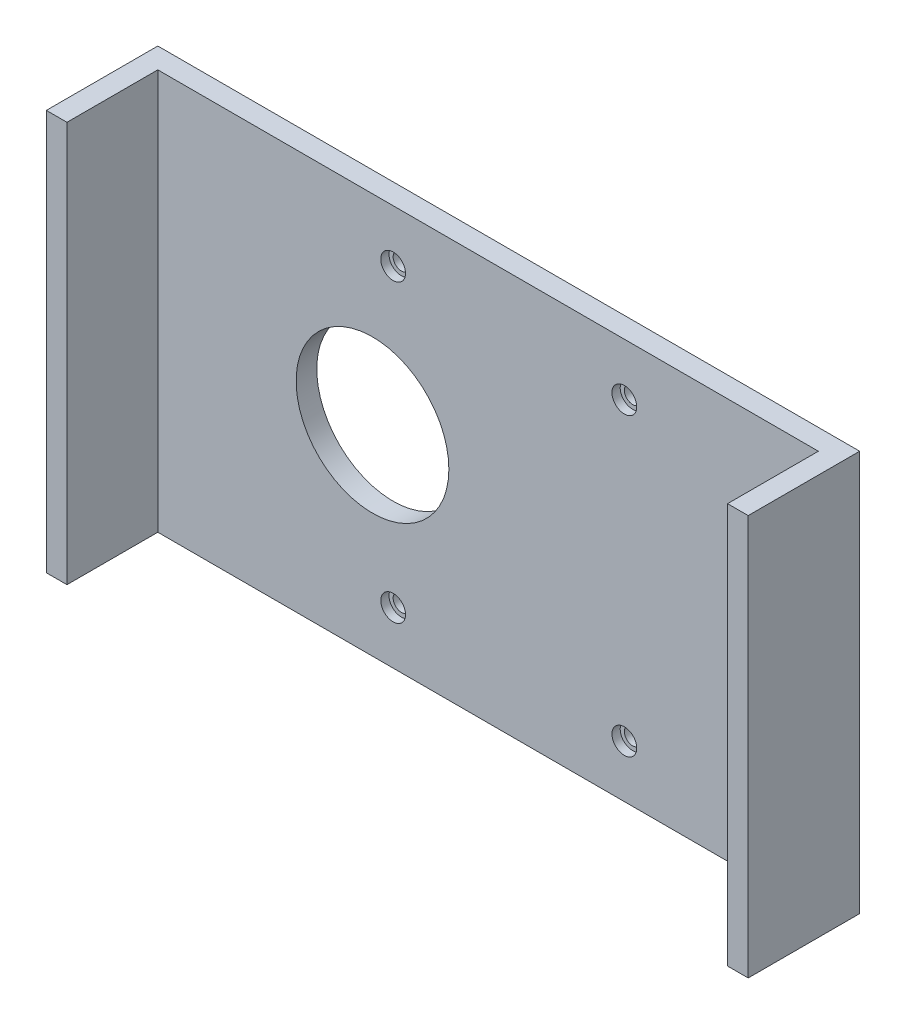
SolidWorks part; units mm, degrees
ref_plane "前视基准面" through (0, 0, 0) normal (0, 0, 1) x (1, 0, 0)
ref_plane "上视基准面" through (0, 0, 0) normal (0, 1, 0) x (1, 0, 0)
ref_plane "右视基准面" through (0, 0, 0) normal (1, 0, 0) x (0, 0, -1)
sketch "草图1" plane through (0, 0, 0) normal (0, 0, 1) x (1, 0, 0)
  line L1 (-170, 0) -> (0, 0)
  line L2 (-170, 0) -> (-170, -97)
  line L3 (-170, -97) -> (0, -97)
  line L4 (0, 0) -> (0, -97)
  point P4 (0, 0)
  dimension "D1" = 170
  dimension "D2" = 97
extrude "凸台-拉伸1" add sketch "草图1" along normal blind 27
sketch "草图2" plane through (0, 0, 0) normal (0, 1, 0) x (1, 0, 0)
  line L0 (-165, 22.4225) -> (-165, -44.2613) construction
  line L1 (-170, 0) -> (-165, 0) construction
  line L2 (0, 0) -> (-170, 0) construction
  line L3 (-170, -5) -> (0, -5) construction
  line L4 (-170, -27) -> (-170, 0) construction
  line L5 (0, -27) -> (0, 0) construction
  line L6 (-5, 8.8963) -> (-5, -58.8963) construction
  line L7 (0, 0) -> (-5, 0) construction
  line L8 (-170, 0) -> (-170, -5) construction
  line L9 (-162.8656, -27) -> (-162.8656, -25) construction
  line L10 (-165, -5) -> (-5, -5)
  line L11 (-165, -5) -> (-165, -25)
  line L13 (-5, -5) -> (-5, -25)
  line L14 (0, -27) -> (-170, -27) construction
  line L15 (-165, -25) -> (-163, -25)
  line L16 (-163, -25) -> (-163, -27)
  line L17 (-5, -25) -> (-7, -25)
  line L18 (-7, -25) -> (-7, -27)
  line M18 (-170, -27) -> (0, -27)
  dimension "D1" = 5
  dimension "D2" = 5
  dimension "D3" = 5
  dimension "D4" = 2
  dimension "D5" = 2
  dimension "D6" = 2
extrude "切除-拉伸1" cut sketch "草图2" against normal through all and the other way through all contours L18 L17 L13 L10 L11 L15 L16 M18
sketch "草图4" plane through (0, 0, 0) normal (0, 1, 0) x (1, 0, 0)
  line L0 (-165, -25) -> (-165, -27)
  line L1 (-163, -27) -> (-170, -27) construction
  line L2 (-5, -25) -> (-5, -27)
  line L3 (0, -27) -> (-7, -27) construction
  line L5 (-165, -25) -> (-163, -25)
  line L6 (-165, -25) -> (-165, -27)
  line L7 (-165, -27) -> (-163, -27)
  line L8 (-163, -25) -> (-163, -27)
  line L9 (-7, -25) -> (-5, -25)
  line L10 (-7, -25) -> (-7, -27)
  line L11 (-7, -27) -> (-5, -27)
  line L12 (-5, -25) -> (-5, -27)
  line M1 (-7, -25) -> (-7, -27)
  line M2 (-7, -27) -> (0, -27)
  line M6 (-170, -27) -> (-163, -27)
  line M7 (-163, -27) -> (-163, -25)
  line M8 (-163, -25) -> (-165, -25)
  line M12 (-5, -25) -> (-7, -25)
extrude "切除-拉伸2" cut sketch "草图4" against normal through all contours L2 M12 M1 M2 | L0 M8 M6 M7
sketch "草图5" plane through (0, 0, 5) normal (0, 0, 1) x (1, 0, 0)
  line L0 (-135, 25.052) -> (-135, -114.3346) construction
  line L1 (-165, 0) -> (-135, 0) construction
  line L2 (-5, 0) -> (-165, 0) construction
  line L3 (-181.0718, -10) -> (17.327, -10) construction
  line L4 (-181.0718, -87) -> (17.327, -87) construction
  line L5 (-108, -15.6363) -> (-52, -15.6363) construction
  line L6 (-52, -15.6363) -> (-52, -4.4608) construction
  line L7 (-144.2482, 0) -> (-144.2482, -10) construction
  line L8 (-143.0679, -87) -> (-143.0679, -97) construction
  line L9 (-165, -97) -> (-5, -97) construction
  line L10 (-113, -10) -> (-113, -87) construction
  line L11 (-135, -11.8896) -> (-113, -11.8896) construction
  line L12 (-135, -84.3) -> (-5, -84.3) construction
  line L13 (-5, -97) -> (-5, 0) construction
  line L14 (-5, -84.3) -> (-5, -87) construction
  line L15 (-5, -97) -> (-5, 0) construction
  line L16 (-135, -12.7) -> (-5, -12.7) construction
  line L17 (-6.7405, -10) -> (-6.7405, -12.7) construction
  line L18 (-135, -15.6363) -> (-108, -15.6363) construction
  line L19 (-108, -15.6363) -> (-108, -4.4608) construction
  line L20 (-135, -83.3343) -> (-108, -83.3343) construction
  line L21 (-108, -83.3343) -> (-108, -92.3616) construction
  line L22 (-108, -83.3343) -> (-52, -83.3343) construction
  line L23 (-52, -83.3343) -> (-52, -94.706) construction
  circle A0 centre (-113, -48.5) radius 18.5
  circle A1 centre (-108, -12.7) radius 2
  circle A2 centre (-108, -84.3) radius 2
  circle A3 centre (-52, -12.7) radius 2
  circle A4 centre (-52, -84.3) radius 2
  dimension "D5" = 37
  dimension "D9" = 4
  dimension "D11" = 4
  dimension "D14" = 4
  dimension "D15" = 4
  dimension "D1" = 30
  dimension "D2" = 10
  dimension "D3" = 10
  dimension "D4" = 22
  dimension "D6" = 2.7
  dimension "D7" = 2.7
  dimension "D8" = 27
  dimension "D10" = 27
  dimension "D12" = 56
  dimension "D13" = 56
extrude "切除-拉伸3" cut sketch "草图5" against normal through all
sketch "草图6" plane through (0, 0, 5) normal (0, 0, 1) x (1, 0, 0)
  circle A0 centre (-108, -12.7) radius 3
  circle A1 centre (-52, -12.7) radius 3
  circle A2 centre (-108, -84.3) radius 3
  circle A3 centre (-52, -84.3) radius 3
  dimension "D1" = 6
  dimension "D2" = 6
  dimension "D3" = 6
  dimension "D4" = 6
extrude "切除-拉伸4" cut sketch "草图6" against normal blind 2
